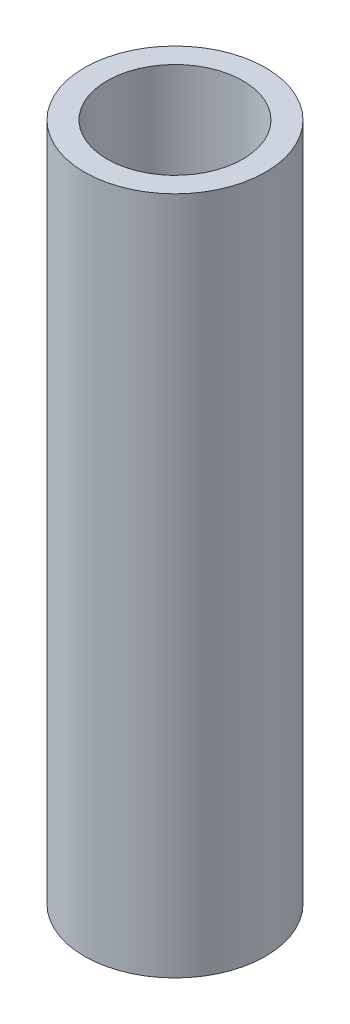
SolidWorks part; units mm, degrees
ref_plane "前视基准面" through (0, 0, 0) normal (0, 0, 1) x (1, 0, 0)
ref_plane "上视基准面" through (0, 0, 0) normal (0, 1, 0) x (1, 0, 0)
ref_plane "右视基准面" through (0, 0, 0) normal (1, 0, 0) x (0, 0, -1)
sketch "草图1" plane through (0, 0, 0) normal (0, 1, 0) x (1, 0, 0)
  circle A0 centre (0, 0) radius 4
  circle A1 centre (0, 0) radius 3
  dimension "D1" = 8
  dimension "D2" = 6
extrude "凸台-拉伸1" add sketch "草图1" along normal blind 30
